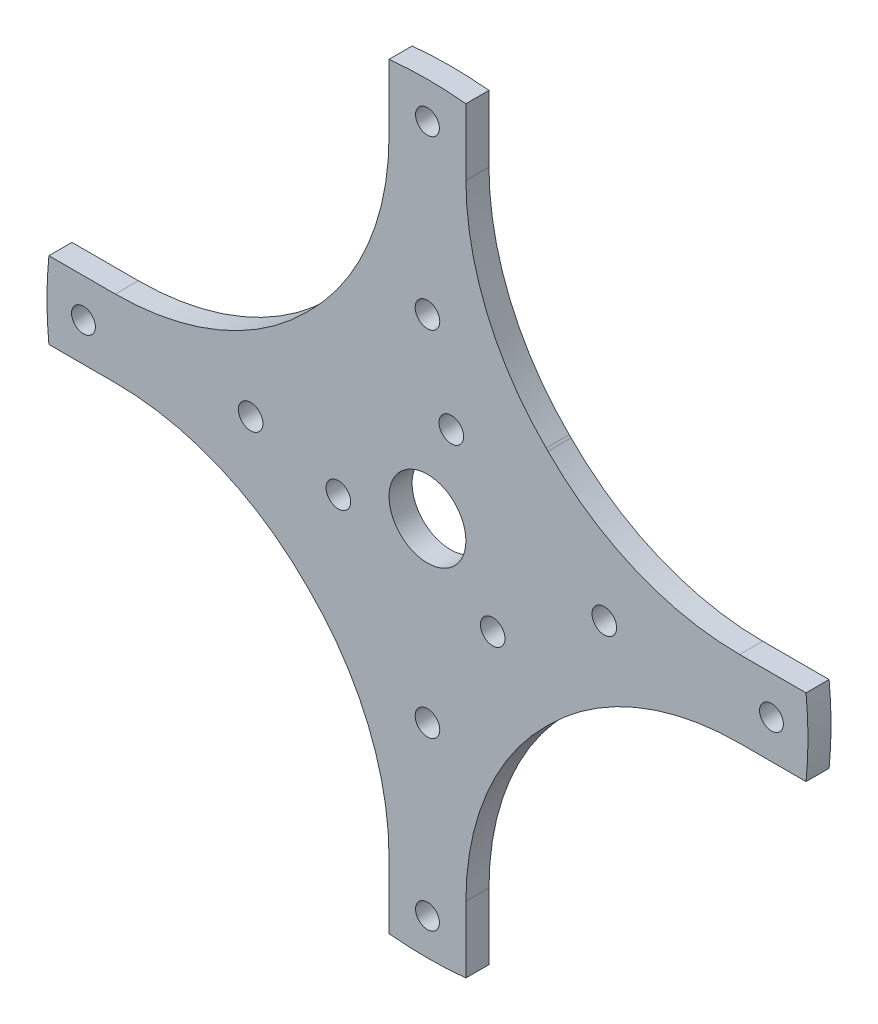
SolidWorks part; units mm, degrees
ref_plane "前视基准面" through (0, 0, 0) normal (0, 0, 1) x (1, 0, 0)
ref_plane "上视基准面" through (0, 0, 0) normal (0, 1, 0) x (1, 0, 0)
ref_plane "右视基准面" through (0, 0, 0) normal (1, 0, 0) x (0, 0, -1)
sketch "草图1" plane through (0, 0, 0) normal (0, 0, 1) x (1, 0, 0)
  line L0 (49.2468, 5) -> (21.4243, 5)
  line L1 (-5, 49.2468) -> (-5, 21.4243)
  line L2 (5, 49.2468) -> (5, 21.4243)
  line L3 (49.2468, -5) -> (21.4243, -5)
  line L4 (5, -49.2468) -> (5, -21.4243)
  line L5 (-5, -49.2468) -> (-5, -21.4243)
  line L6 (-49.2468, -5) -> (-21.4243, -5)
  line L7 (-49.2468, 5) -> (-21.4243, 5)
  line L8 (0, 44.75) -> (0, 32.7432) construction
  circle A0 centre (-44.75, 0) radius 1.55
  circle A1 centre (0, 0) radius 5
  circle A2 centre (0, 44.75) radius 1.55
  circle A3 centre (44.75, 0) radius 1.55
  circle A4 centre (0, -44.75) radius 1.55
  circle A5 centre (3.1058, 11.5911) radius 1.6
  arc A6 (-5, 21.4243) -> (-21.4243, 5) centre (0, 0) ccw
  circle A10 centre (8.4853, -8.4853) radius 1.6
  circle A11 centre (-11.5911, -3.1058) radius 1.6
  arc A12 (-49.2468, 5) -> (-49.2468, -5) centre (0, 0) ccw
  arc A18 (21.4243, 5) -> (5, 21.4243) centre (0, 0) ccw
  arc A19 (5, -21.4243) -> (21.4243, -5) centre (0, 0) ccw
  arc A20 (-21.4243, -5) -> (-5, -21.4243) centre (0, 0) ccw
  arc A21 (5, 49.2468) -> (-5, 49.2468) centre (0, 0) ccw
  arc A22 (49.2468, -5) -> (49.2468, 5) centre (0, 0) ccw
  arc A23 (-5, -49.2468) -> (5, -49.2468) centre (0, 0) ccw
  point P37 (0, 0)
  point P64 (0, 0)
  dimension "D1" = 4
extrude "凸台-拉伸1" add sketch "草图1" along normal blind 3
fillet "圆角1" radius 35 8 edges at (-5, -21.4243, 1.5) (5, -21.4243, 1.5) (21.4243, -5, 1.5) (21.4243, 5, 1.5) (5, 21.4243, 1.5) (-5, 21.4243, 1.5) (-21.4243, 5, 1.5) (-21.4243, -5, 1.5)
sketch "草图2" plane through (0, 0, 3) normal (0, 0, 1) x (1, 0, 0)
  circle A0 centre (0, 0) radius 23 construction
  circle A1 centre (-23, 0) radius 1.6
  circle A2 centre (0, 23) radius 1.6
  circle A3 centre (23, 0) radius 1.6
  circle A4 centre (0, -23) radius 1.6
extrude "切除-拉伸1" cut sketch "草图2" against normal blind 14
